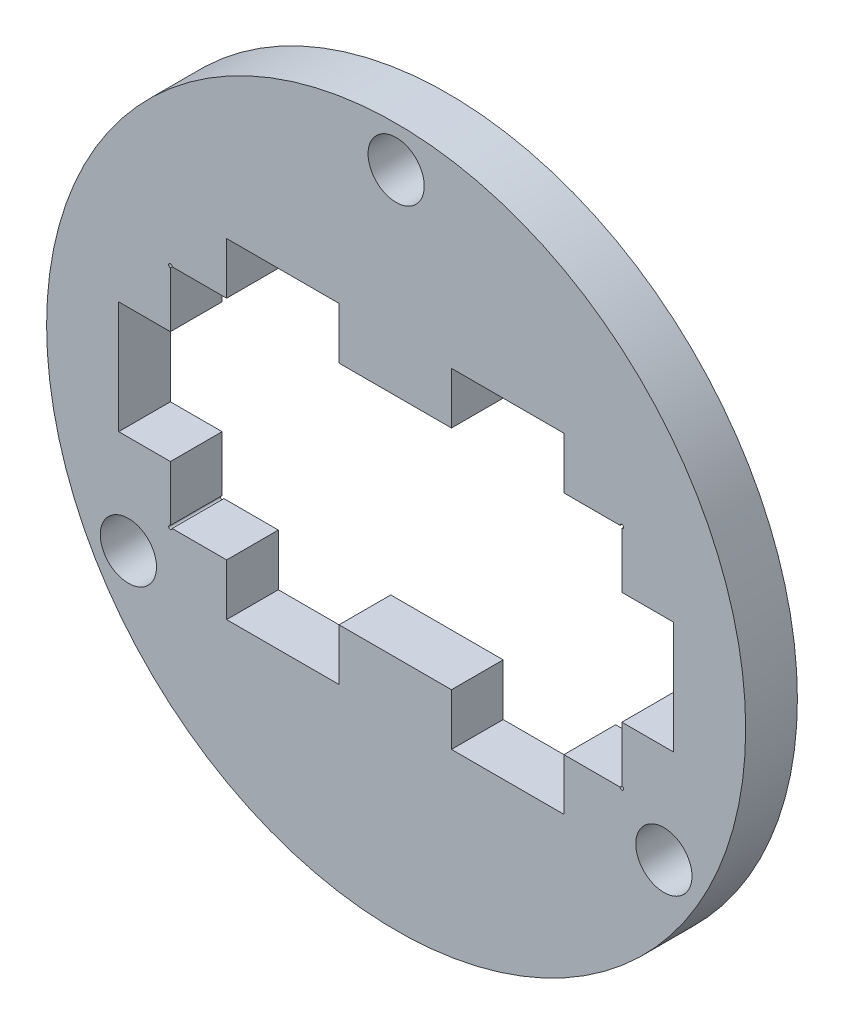
SolidWorks part; units mm, degrees
ref_plane "Front Plane" through (0, 0, 0) normal (0, 0, 1) x (1, 0, 0)
ref_plane "Top Plane" through (0, 0, 0) normal (0, 1, 0) x (1, 0, 0)
ref_plane "Right Plane" through (0, 0, 0) normal (1, 0, 0) x (0, 0, -1)
sketch "Sketch1" plane through (0, 0, 0) normal (0, 0, 1) x (1, 0, 0)
  line L1 (-25.3016, -12.8) -> (25.3016, -12.8)
  line L2 (-25.5, -12.6016) -> (-25.5, 12.6016)
  line L3 (-25.3016, 12.8) -> (25.3016, 12.8)
  line L4 (25.5, -12.6016) -> (25.5, 12.6016)
  line L5 (-25.5, -12.8) -> (25.5, 12.8) construction
  line L6 (-25.5, 12.8) -> (25.5, -12.8) construction
  circle A0 centre (0, 34.925) radius 3.175
  circle A1 centre (0, 34.925) radius 4.7625 construction
  circle A2 centre (30.2459, -17.4625) radius 6.35 construction
  circle A3 centre (30.2459, -17.4625) radius 4.7625 construction
  circle A4 centre (30.2459, -17.4625) radius 3.175
  circle A5 centre (-30.2459, -17.4625) radius 6.35 construction
  circle A6 centre (0, 0) radius 41.275
  circle A7 centre (0, 34.925) radius 6.35 construction
  circle A8 centre (-30.2459, -17.4625) radius 4.7625 construction
  circle A9 centre (-30.2459, -17.4625) radius 3.175
  arc A10 (25.5, 12.6016) -> (25.3016, 12.8) centre (25.5, 12.8) ccw
  arc A11 (25.3016, -12.8) -> (25.5, -12.6016) centre (25.5, -12.8) ccw
  arc A12 (-25.3016, 12.8) -> (-25.5, 12.6016) centre (-25.5, 12.8) ccw
  arc A13 (-25.5, -12.6016) -> (-25.3016, -12.8) centre (-25.5, -12.8) ccw
  point P0 (0, 0)
  point P25 (0, 0)
  dimension "D3" = 1.5875
  dimension "D6" = 6.35
  dimension "D1" = 82.55
  dimension "D2" = 34.925
  dimension "D4" = 51
  dimension "D5" = 25.6
extrude "Boss-Extrude1" add sketch "Sketch1" along normal blind 5.842
sketch "Sketch7" plane through (0, 0, 0) normal (0, 0, -1) x (-1, 0, 0)
  circle A0 centre (0, 0) radius 41.275
  circle A1 centre (0, 0) radius 39.4875
  dimension "D1" = 78.975
extrude "Cut-Extrude3" cut sketch "Sketch7" against normal through all
sketch "Sketch8" plane through (0, 0, 0) normal (0, 0, -1) x (-1, 0, 0)
  line L0 (25.3016, 12.8) -> (-25.3016, 12.8) construction
  line L3 (0, 0) -> (39.4875, 0) construction
  line L4 (-25.5, -12.6016) -> (-25.5, 12.6016) construction
  line L5 (-31.342, -6.35) -> (-25.5, -6.35)
  line L6 (-31.342, -6.35) -> (-31.342, 6.35)
  line L7 (-18.95, 12.8) -> (-6.25, 12.8)
  line L8 (-18.95, 12.8) -> (-18.95, 18.642)
  line L9 (-18.95, 18.642) -> (-6.25, 18.642)
  line L10 (-6.25, 12.8) -> (-6.25, 18.642)
  line L11 (-18.95, 12.8) -> (-6.25, 18.642) construction
  line L12 (-18.95, 18.642) -> (-6.25, 12.8) construction
  line L13 (19.15, 18.642) -> (6.45, 12.8) construction
  line L14 (19.15, 12.8) -> (6.45, 18.642) construction
  line L15 (6.45, 12.8) -> (6.45, 18.642)
  line L16 (19.15, 18.642) -> (6.45, 18.642)
  line L17 (19.15, 12.8) -> (19.15, 18.642)
  line L18 (19.15, 12.8) -> (6.45, 12.8)
  line L19 (0, 0) -> (-39.4875, 0) construction
  line L20 (19.15, -12.8) -> (6.45, -18.642) construction
  line L21 (19.15, -18.642) -> (6.45, -12.8) construction
  line L22 (-18.95, -18.642) -> (-6.25, -12.8) construction
  line L23 (-18.95, -12.8) -> (-6.25, -18.642) construction
  line L24 (19.15, -12.8) -> (6.45, -12.8)
  line L25 (19.15, -12.8) -> (19.15, -18.642)
  line L26 (19.15, -18.642) -> (6.45, -18.642)
  line L27 (6.45, -12.8) -> (6.45, -18.642)
  line L28 (-6.25, -12.8) -> (-6.25, -18.642)
  line L29 (-18.95, -18.642) -> (-6.25, -18.642)
  line L30 (-18.95, -12.8) -> (-18.95, -18.642)
  line L31 (-18.95, -12.8) -> (-6.25, -12.8)
  line L32 (-31.342, 6.35) -> (-25.5, 6.35)
  line L33 (-25.5, -6.35) -> (-25.5, 6.35)
  line L34 (-31.342, -6.35) -> (-25.5, 6.35) construction
  line L35 (-31.342, 6.35) -> (-25.5, -6.35) construction
  line L36 (0, 12.8) -> (0, -12.8) construction
  line L37 (25.3016, -12.8) -> (-25.3016, -12.8) construction
  line L38 (31.342, 6.35) -> (25.5, -6.35) construction
  line L39 (31.342, -6.35) -> (25.5, 6.35) construction
  line L40 (25.5, -6.35) -> (25.5, 6.35)
  line L41 (31.342, 6.35) -> (25.5, 6.35)
  line L42 (31.342, -6.35) -> (31.342, 6.35)
  line L43 (31.342, -6.35) -> (25.5, -6.35)
  circle A0 centre (0, 0) radius 39.4875 construction
  point P12 (-12.6, 15.721)
  point P19 (12.8, 15.821)
  point P25 (12.8, -15.821)
  point P26 (-12.6, -15.721)
  point P27 (-28.421, 0)
  point P44 (28.421, 0)
  dimension "D1" = 12.7
  dimension "D2" = 5.842
  dimension "D3" = 5.842
  dimension "D4" = 12.7
extrude "Cut-Extrude4" cut sketch "Sketch8" against normal through all
